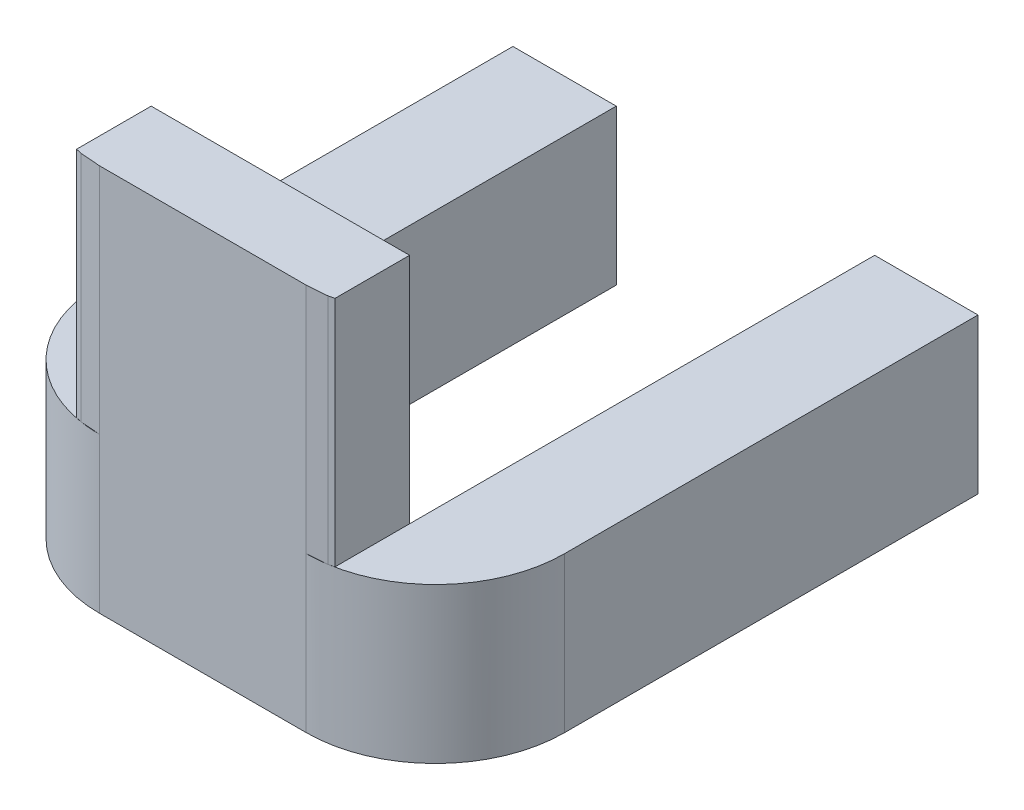
SolidWorks part; units mm, degrees
ref_plane "Front Plane" through (0, 0, 0) normal (0, 0, 1) x (1, 0, 0)
ref_plane "Top Plane" through (0, 0, 0) normal (0, 1, 0) x (1, 0, 0)
ref_plane "Right Plane" through (0, 0, 0) normal (1, 0, 0) x (0, 0, -1)
sketch "Sketch1" plane through (0, 0, 0) normal (0, 1, 0) x (1, 0, 0)
  line L0 (9, 21) -> (9, 0)
  line L1 (-5, 3) -> (5, 3)
  line L4 (5, 3) -> (5, 16)
  line L5 (-5, 21) -> (-5, 16)
  line L6 (-9, 21) -> (-5, 21)
  line L7 (9, 0) -> (-9, 0)
  line L8 (9, 21) -> (5, 21)
  line L9 (0, 3) -> (0, 0) construction
  line L10 (5, 21) -> (5, 16)
  line L11 (-5, 3) -> (-5, 16)
  line L12 (-9, 21) -> (-9, 0)
  point P0 (0, 0)
  dimension "D1" = 4
  dimension "D2" = 18
  dimension "D3" = 5
  dimension "D4" = 3
extrude "Boss-Extrude1" add sketch "Sketch1" along normal blind 6
sketch "Sketch4" plane through (0, 0, -21) normal (0, 0, -1) x (-1, 0, 0)
  line L1 (9, 6) -> (9, 0) construction
  line L2 (0, 0) -> (0, 6) construction
  line L3 (-5, 6) -> (5, 6) construction
  line L4 (0, 3) -> (9, 3) construction
  circle A0 centre (7, 3) radius 1.5
  circle A1 centre (-7, 3) radius 1.5
  dimension "D1" = 3
  dimension "D3" = 2
extrude "Cut-Extrude3" cut sketch "Sketch4" against normal blind 4
fillet "Fillet1" radius 5 2 edges at (9, 3, 0) (-9, 3, 0)
sketch "Sketch5" plane through (0, 0, 0) normal (0, -1, 0) x (1, 0, 0)
  line L0 (-4, 0) -> (-4.7839, -0.0618)
  line L1 (-5, -3) -> (5, -3)
  line L2 (-5, -3) -> (-5, 0)
  line L3 (-5, 0) -> (5, 0)
  line L4 (5, -3) -> (5, 0)
  line L5 (-4, 0) -> (-4.7839, -0.0618)
  line L6 (-4.7839, -0.0618) -> (-5, -0.1132)
  line L7 (4.7839, -0.0618) -> (4, 0)
  line L9 (0, -3.3) -> (0, 3.3) construction
  line L10 (4.7839, -0.0618) -> (5, -0.1132)
  line L13 (5, -3) -> (-5, -3) construction
  arc A0 (-4, 0) -> (-9, -5) centre (-4, -5) ccw construction
  line M10 (4, 0) -> (-4, 0)
  line M15 (-5, -3) -> (5, -3)
extrude "Boss-Extrude2" add sketch "Sketch5" against normal blind 15 contours L10 L7 L0 L6 L2 L4 M10 M15
